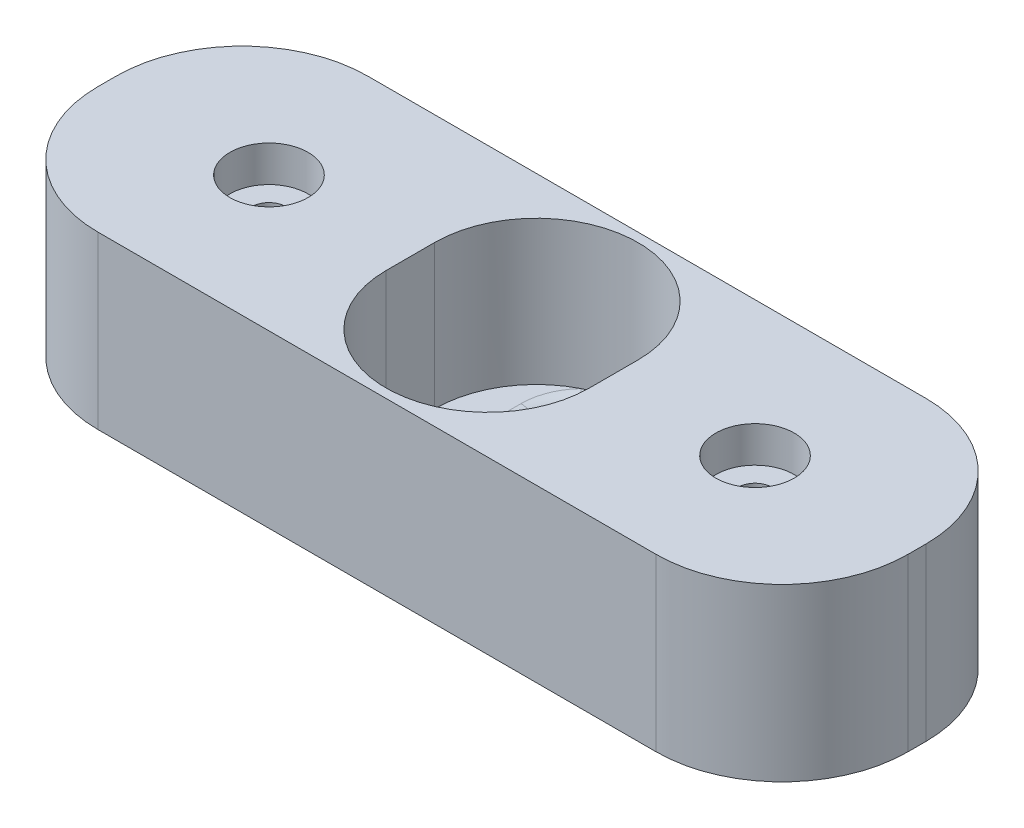
SolidWorks part; units mm, degrees
ref_plane "Front Plane" through (0, 0, 0) normal (0, 0, 1) x (1, 0, 0)
ref_plane "Top Plane" through (0, 0, 0) normal (0, 1, 0) x (1, 0, 0)
ref_plane "Right Plane" through (0, 0, 0) normal (1, 0, 0) x (0, 0, -1)
sketch "Sketch1" plane through (0, 0, 0) normal (0, 1, 0) x (1, 0, 0)
  line L1 (0, 0) -> (45, 0)
  line L2 (0, 0) -> (0, 15)
  line L3 (0, 15) -> (45, 15)
  line L4 (45, 0) -> (45, 15)
  dimension "D1" = 45
  dimension "D2" = 15
extrude "Boss-Extrude1" add sketch "Sketch1" against normal blind 9.5
sketch "Sketch8" plane through (0, 0, 0) normal (0, 1, 0) x (1, 0, 0)
  line L0 (45, 15) -> (0, 0) construction
  line L1 (0, 15) -> (45, 0) construction
  line L2 (45, 8.85) -> (0, 8.85) construction
  line L3 (45, 0) -> (45, 15) construction
  line L4 (0, 15) -> (0, 0) construction
  line L5 (0, 6.15) -> (45, 6.15) construction
  line L6 (22.5, 0) -> (22.5, 6.15) construction
  line L7 (0, 0) -> (45, 0) construction
  line L8 (22.5, 15) -> (22.5, 8.85) construction
  line L9 (45, 15) -> (0, 15) construction
  line L10 (16.85, 8.85) -> (16.85, 6.15)
  line L11 (28.15, 8.85) -> (28.15, 6.15)
  line L12 (22.5, 7.5) -> (16.85, 7.5) construction
  line L13 (22.5, 7.5) -> (28.15, 7.5) construction
  arc A0 (28.15, 8.85) -> (16.85, 8.85) centre (22.5, 8.85) ccw
  arc A1 (16.85, 6.15) -> (28.15, 6.15) centre (22.5, 6.15) ccw
  dimension "D1" = 6.15
  dimension "D2" = 5.65
sketch "Sketch2" plane through (0, 0, 0) normal (0, 1, 0) x (1, 0, 0)
  line L0 (45, 15) -> (0, 15) construction
  line L1 (0, 15) -> (0, 0) construction
  circle A0 centre (22.5, 8.82) radius 5.5
  dimension "D2" = 11
  dimension "D1" = 6.18
  dimension "D3" = 22.5
extrude "Cut-Extrude1" cut sketch "Sketch2" against normal blind 8
extrude "Cut-Extrude6" cut sketch "Sketch8" against normal blind 8
sketch "Sketch3" plane through (0, -8, 0) normal (0, 1, 0) x (1, 0, 0)
  line L0 (45, 15) -> (0, 0) construction
  line L3 (0, 15) -> (45, 0) construction
  line L4 (45, 11.5) -> (0, 11.5) construction
  line L5 (0, 3.5) -> (45, 3.5) construction
  line L6 (22.5, 0) -> (22.5, 3.5) construction
  line L7 (22.5, 15) -> (22.5, 11.5) construction
  line L8 (20, 11.5) -> (20, 3.5)
  line L9 (25, 11.5) -> (25, 3.5)
  line L10 (22.5, 7.5) -> (20, 7.5) construction
  line L11 (22.5, 7.5) -> (25, 7.5) construction
  line L12 (0, 15) -> (0, 0) construction
  line L13 (45, 15) -> (0, 15) construction
  arc A1 (25, 11.5) -> (20, 11.5) centre (22.5, 11.5) ccw
  arc A2 (20, 3.5) -> (25, 3.5) centre (22.5, 3.5) ccw
  point P42 (22.5, 15)
  dimension "D1" = 2.5
  dimension "D2" = 3.5
extrude "Cut-Extrude2" cut sketch "Sketch3" against normal up to next
sketch "Sketch4" plane through (0, 0, 0) normal (0, 1, 0) x (1, 0, 0)
  line L0 (45, 15) -> (0, 15) construction
  line L1 (9, 7.5) -> (22.5, 7.5) construction
  line L2 (22.5, 7.5) -> (36, 7.5) construction
  line L3 (22.5, 14) -> (22.5, 1) construction
  circle A0 centre (9, 7.5) radius 2.175
  circle A1 centre (36, 7.5) radius 2.175
  arc A4 (25, 11.5) -> (20, 11.5) centre (22.5, 11.5) ccw construction
  arc A5 (20, 3.5) -> (25, 3.5) centre (22.5, 3.5) ccw construction
  dimension "D3" = 4.35
  dimension "D4" = 13.5
  dimension "D1" = 7.5
  dimension "D2" = 7.5
extrude "Cut-Extrude3" cut sketch "Sketch4" against normal blind 2
fillet "Fillet1" radius 7 4 edges at (45, -4.75, -15) (0, -4.75, -15) (45, -4.75, 0) (0, -4.75, 0)
sketch "Sketch5" plane through (0, -9.5, 0) normal (0, -1, 0) x (-1, 0, 0)
  line L0 (-38, 15) -> (-7, 15) construction
  line L1 (-22.5, 1) -> (-22.5, 14) construction
  line L2 (-9, 7.5) -> (-22.5, 7.5) construction
  line L3 (-22.5, 7.5) -> (-36, 7.5) construction
  circle A0 centre (-36, 7.5) radius 2.05
  circle A1 centre (-9, 7.5) radius 2.05
  arc A3 (-25, 3.5) -> (-20, 3.5) centre (-22.5, 3.5) ccw construction
  arc A4 (-20, 11.5) -> (-25, 11.5) centre (-22.5, 11.5) ccw construction
  point P21 (-22.5, 7.5)
  dimension "D5" = 4.1
  dimension "D1" = 7.5
  dimension "D2" = 7.5
  dimension "D3" = 13.5
extrude "Cut-Extrude4" cut sketch "Sketch5" against normal blind 5
sketch "Sketch6" plane through (0, -2, 0) normal (0, 1, 0) x (1, 0, 0)
  circle A1 centre (9, 7.5) radius 0.95
  circle A2 centre (36, 7.5) radius 0.95
  dimension "D1" = 1.9
extrude "Cut-Extrude5" cut sketch "Sketch6" against normal blind 3
fillet "Fillet3" radius 1 4 edges at (22.5, -8, -14) (25, -8, -7.5) (22.5, -8, -1) (20, -8, -7.5)
